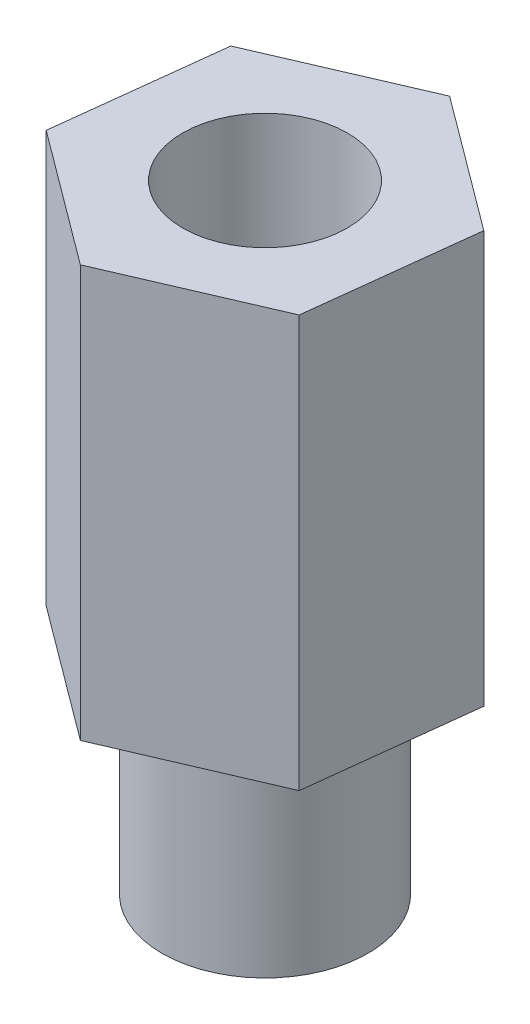
SolidWorks part; units mm, degrees
ref_plane "前视基准面" through (0, 0, 0) normal (0, 0, 1) x (1, 0, 0)
ref_plane "上视基准面" through (0, 0, 0) normal (0, 1, 0) x (1, 0, 0)
ref_plane "右视基准面" through (0, 0, 0) normal (1, 0, 0) x (0, 0, -1)
sketch "草图1" plane through (0, 0, 0) normal (0, 1, 0) x (1, 0, 0)
  circle A0 centre (0, 0) radius 5
  dimension "D1" = 10
extrude "凸台-拉伸1" add sketch "草图1" along normal blind 10
sketch "草图2" plane through (0, 10, 0) normal (0, 1, 0) x (1, 0, 0)
  line L1 (7.421, 3.2034) -> (0.9363, 8.0285)
  line L2 (0.9363, 8.0285) -> (-6.4847, 4.8251)
  line L3 (-6.4847, 4.8251) -> (-7.421, -3.2034)
  line L4 (-7.421, -3.2034) -> (-0.9363, -8.0285)
  line L5 (-0.9363, -8.0285) -> (6.4847, -4.8251)
  line L6 (6.4847, -4.8251) -> (7.421, 3.2034)
  circle A0 centre (0, 0) radius 7 construction
  dimension "D1" = 14
extrude "凸台-拉伸2" add sketch "草图2" along normal blind 20
sketch "草图3" plane through (0, 30, 0) normal (0, 1, 0) x (1, 0, 0)
  circle A0 centre (0, 0) radius 4
  dimension "D1" = 8
extrude "切除-拉伸1" cut sketch "草图3" against normal through all
